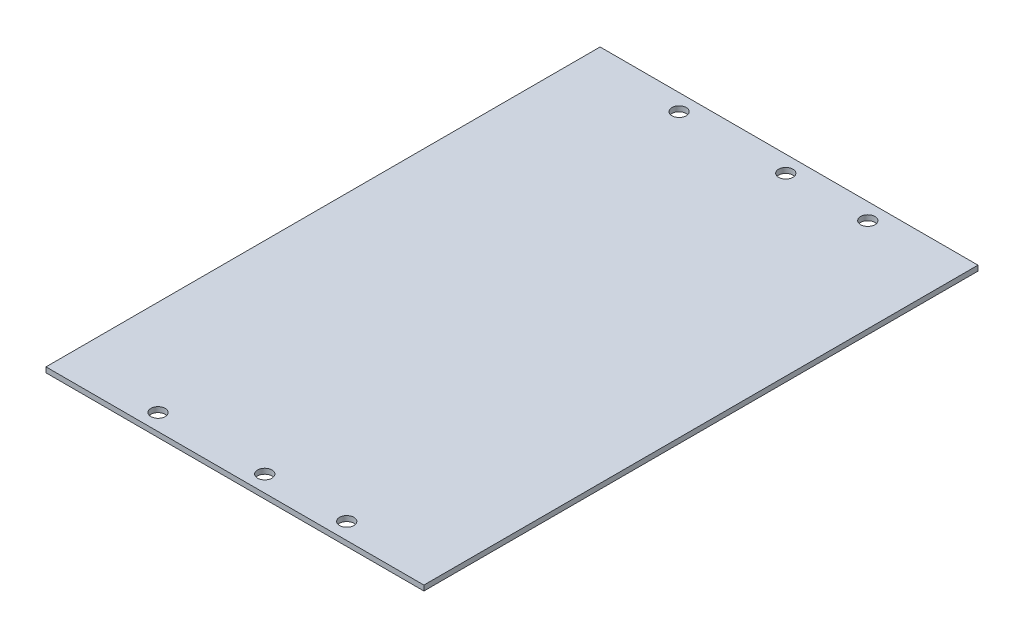
SolidWorks part; units mm, degrees
material "Zoltek Panex 33"
ref_plane "Front Plane" through (0, 0, 0) normal (0, 0, 1) x (1, 0, 0)
ref_plane "Top Plane" through (0, 0, 0) normal (0, 1, 0) x (1, 0, 0)
ref_plane "Right Plane" through (0, 0, 0) normal (1, 0, 0) x (0, 0, -1)
sketch "Sketch1" plane through (0, 0, 0) normal (0, 1, 0) x (1, 0, 0)
  line L0 (138.9, 214.3) -> (138.9, 202.3) construction
  line L5 (18.4, 202.3) -> (18.4, 214.3) construction
  line L6 (136.9, 1.405) -> (20.4, 1.405) construction
  line L7 (83.4, 163.4515) -> (83.4, 52.2535) construction
  line L8 (43.9375, 107.8525) -> (122.8625, 107.8525) construction
  line L9 (5.7, 1.405) -> (150.9, 1.405)
  line L10 (5.7, 1.405) -> (5.7, 214.3)
  line L11 (5.7, 214.3) -> (150.9, 214.3)
  line L12 (150.9, 1.405) -> (150.9, 214.3)
  line L13 (136.9, 214.3) -> (20.4, 214.3) construction
  line L14 (150.9, -29.595) -> (150.9, 246) construction
  line L15 (18.4, 1.405) -> (18.4, 13.405) construction
  circle A0 centre (42.4, 207.95) radius 2.75
  circle A1 centre (83.4, 207.95) radius 2.75
  circle A2 centre (114.9, 207.95) radius 2.75
  circle A3 centre (114.9, 7.755) radius 2.75
  circle A4 centre (83.4, 7.755) radius 2.75
  circle A5 centre (42.4, 7.755) radius 2.75
  dimension "D4" = 5.5
  dimension "D5" = 24
  dimension "D6" = 24
  dimension "D7" = 0
  dimension "D2" = 6.35
  dimension "D1" = 12.7
extrude "Boss-Extrude1" add sketch "Sketch1" along normal blind 2
